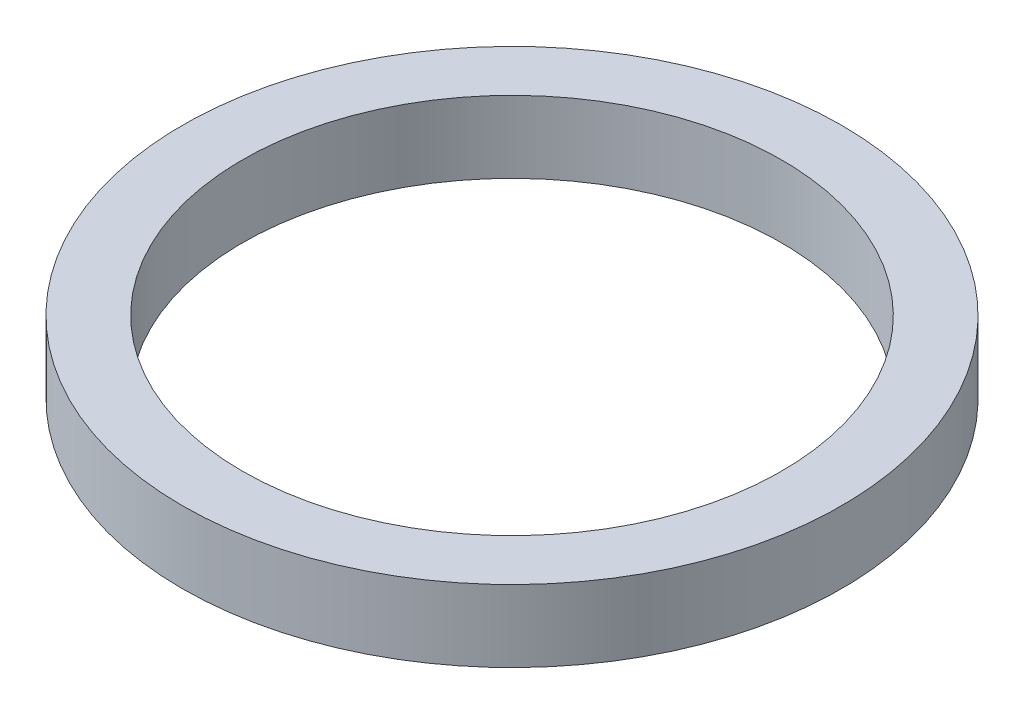
SolidWorks part; units mm, degrees
material "6061-T6 (SS)"
ref_plane "Front Plane" through (0, 0, 0) normal (0, 0, 1) x (1, 0, 0)
ref_plane "Top Plane" through (0, 0, 0) normal (0, 1, 0) x (1, 0, 0)
ref_plane "Right Plane" through (0, 0, 0) normal (1, 0, 0) x (0, 0, -1)
sketch "Sketch1" plane through (0, 0, 0) normal (0, 1, 0) x (1, 0, 0)
  circle A0 centre (0, 0) radius 22.5
  circle A1 centre (0, 0) radius 27.5
  dimension "D1" = 45
  dimension "D2" = 55
extrude "Boss-Extrude1" add sketch "Sketch1" along normal mid plane 6
